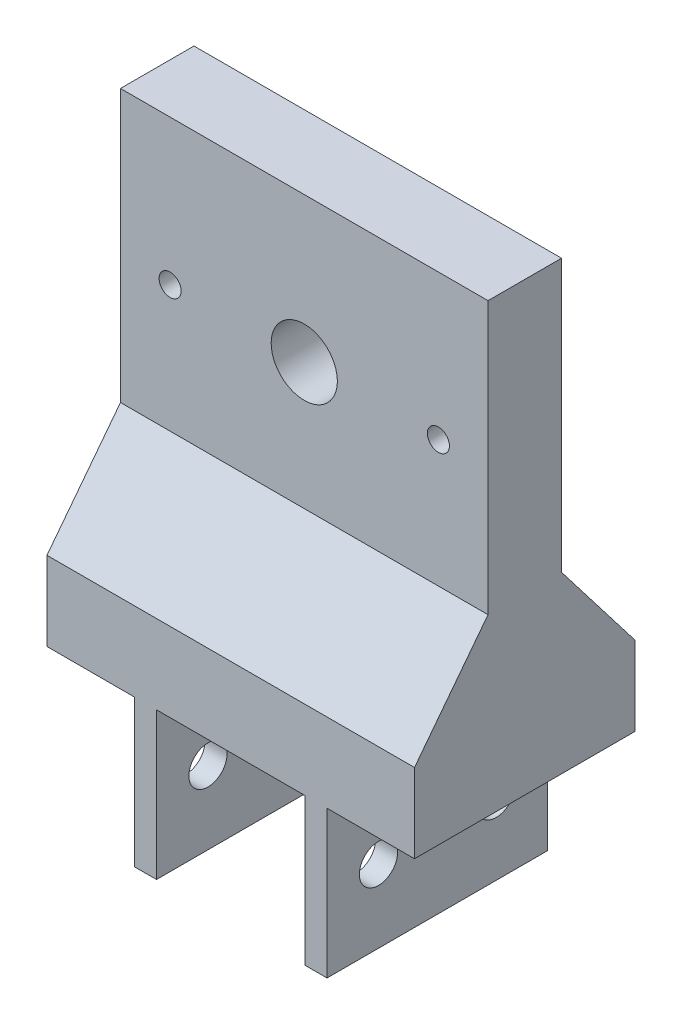
SolidWorks part; units mm, degrees
ref_plane "前视基准面" through (0, 0, 0) normal (0, 0, 1) x (1, 0, 0)
ref_plane "上视基准面" through (0, 0, 0) normal (0, 1, 0) x (1, 0, 0)
ref_plane "右视基准面" through (0, 0, 0) normal (1, 0, 0) x (0, 0, -1)
other "Configuration Table"
sketch "草图1" plane through (0, 0, 0) normal (0, 0, 1) x (1, 0, 0)
  line L0 (0, -39.6057) -> (0, 25.2485) construction
  line L9 (10.1, -25.375) -> (13.1, -25.375)
  line L10 (-25, -5.375) -> (-13.1, -5.375)
  line L11 (-25, -5.375) -> (-25, 5.375)
  line L12 (-25, 5.375) -> (25, 5.375)
  line L13 (25, -5.375) -> (25, 5.375)
  line L14 (-25, -5.375) -> (25, 5.375) construction
  line L15 (-25, 5.375) -> (25, -5.375) construction
  line L16 (-10.1, -5.375) -> (10.1, -5.375)
  line L17 (-13.1, -5.375) -> (-13.1, -25.375)
  line L18 (-13.1, -25.375) -> (-10.1, -25.375)
  line L19 (13.1, -5.375) -> (13.1, -25.375)
  line L21 (-10.1, -25.375) -> (-10.1, -5.375)
  line L22 (-10.1, -5.375) -> (10.1, -5.375)
  line L23 (10.1, -25.375) -> (10.1, -5.375)
  line L24 (-8.4435, -45.2703) -> (10.1, -5.375) construction
  line L25 (-10.1, -5.375) -> (10.5079, -49.7116) construction
  line L26 (-10.1, -5.375) -> (10.1, -5.375)
  line L27 (13.1, -5.375) -> (25, -5.375)
  point P2 (0, 0)
  point P12 (0, -27.1045)
  dimension "D1" = 50
  dimension "D2" = 10.75
  dimension "D3" = 20
  dimension "D4" = 3
  dimension "D5" = 20.2
extrude "凸台-拉伸1" add sketch "草图1" along normal blind 30 contours L19 L27 L13 L12 L11 L10 L17 L18 L21 L16 L23 L9
sketch "草图2" plane through (0, 5.375, 0) normal (0, 1, 0) x (1, 0, 0)
  line L5 (-25, -30) -> (-25, 0) construction
  line L6 (-25, -10) -> (25, -10)
  line L7 (-25, -10) -> (-25, -20)
  line L8 (-25, -20) -> (25, -20)
  line L9 (25, -10) -> (25, -20)
  line L10 (25, -30) -> (25, 0) construction
  line L11 (-25, 0) -> (25, 0) construction
  dimension "D1" = 10
  dimension "D2" = 10
extrude "凸台-拉伸2" add sketch "草图2" along normal blind 50
hole_wizard "孔2" positions "草图8" profile "草图9" legacy end condition through all
sketch "草图8" plane through (-13.1, 0, 0) normal (-1, 0, 0) x (0, 0, 1)
  line L0 (30, -5.375) -> (0, -5.375) construction
  line L1 (0, -5.375) -> (0, -25.375) construction
  line L2 (30, -5.375) -> (30, -25.375) construction
  point P0 (7, -15.375)
  point P2 (23, -15.375)
  dimension "D1" = 10
  dimension "D2" = 10
  dimension "D3" = 7
  dimension "D4" = 7
sketch "草图9" plane through (-13.1, -15.375, 7) normal (0, 1, 0) x (0, 0, 1)
  line L0 (0, 0) -> (0, 38.1)
  line L1 (0, 38.1) -> (2.6, 38.1)
  line L2 (2.6, 38.1) -> (2.6, 0)
  line L3 (2.6, 0) -> (0, 0)
  line L4 (0, 110) -> (0, -10) construction
  dimension "直径" = 5.2
  dimension "深度" = 38.1
hole_wizard "孔3" positions "草图12" profile "草图13" legacy end condition through all
sketch "草图12" plane through (0, 0, 10) normal (0, 0, -1) x (-1, 0, 0)
  line L0 (0, 55.375) -> (0, 5.375) construction
  line L1 (-25, 55.375) -> (25, 55.375) construction
  line L2 (25, 5.375) -> (-25, 5.375) construction
  line L4 (-25, 5.375) -> (25, 5.375) construction
  point P0 (0, 35.625)
  point P11 (0, 34.1146)
  dimension "D1" = 30.25
sketch "草图13" plane through (0, 35.625, 10) normal (1, 0, 0) x (0, 1, 0)
  line L0 (0, 0) -> (0, 20)
  line L1 (0, 20) -> (4.5, 20)
  line L2 (4.5, 20) -> (4.5, 0)
  line L3 (4.5, 0) -> (0, 0)
  line L4 (0, 110) -> (0, -10) construction
  dimension "直径" = 9
  dimension "深度" = 20
sketch "草图17" plane through (0, 0, 10) normal (0, 0, -1) x (-1, 0, 0)
  line L0 (0, 55.375) -> (0, 5.375) construction
  line L1 (-25, 55.375) -> (25, 55.375) construction
  line L2 (25, 5.375) -> (-25, 5.375) construction
  line L3 (-25.3813, 35.625) -> (25.3813, 35.625) construction
  circle A0 centre (18.25, 35.625) radius 2.45
  circle A1 centre (-18.25, 35.625) radius 2.45
  point P10 (0, 35.625)
  point P14 (0, 0)
  dimension "D1" = 4.9
  dimension "D2" = 4.9
  dimension "D3" = 36.5
extrude "凸台-拉伸6" add sketch "草图17" along normal blind 4
hole_wizard "孔5" positions "草图18" profile "草图19" legacy end condition through all
sketch "草图18" plane through (0, 0, 6) normal (0, 0, -1) x (-1, 0, 0)
  point P0 (18.25, 35.625)
  point P3 (-18.25, 35.625)
sketch "草图19" plane through (-18.25, 35.625, 6) normal (1, 0, 0) x (0, 1, 0)
  line L0 (0, 0) -> (0, 24)
  line L1 (0, 24) -> (1.5, 24)
  line L2 (1.5, 24) -> (1.5, 0)
  line L3 (1.5, 0) -> (0, 0)
  line L4 (0, 110) -> (0, -10) construction
  dimension "直径" = 3
  dimension "深度" = 24
sketch "草图20" plane through (-25, 0, 0) normal (-1, 0, 0) x (0, 0, 1)
  line L0 (20, 18.375) -> (30, 5.375)
  line L1 (20, 55.375) -> (20, 5.375) construction
  line L2 (30, -5.375) -> (30, 5.375) construction
  line L3 (30, 5.375) -> (20, 5.375) construction
  line L4 (30, 5.375) -> (20, 5.375)
  line L5 (20, 5.375) -> (20, 18.375)
  line L6 (10, 18.375) -> (0, 5.375)
  line L7 (10, 55.375) -> (10, 5.375) construction
  line L8 (0, 5.375) -> (10, 5.375)
  line L9 (10, 5.375) -> (10, 18.375)
  point P15 (0, 0)
  dimension "D1" = 13
extrude "凸台-拉伸7" add sketch "草图20" against normal up to surface (50 mm away) up to face at (25, 15.1875, 15)
